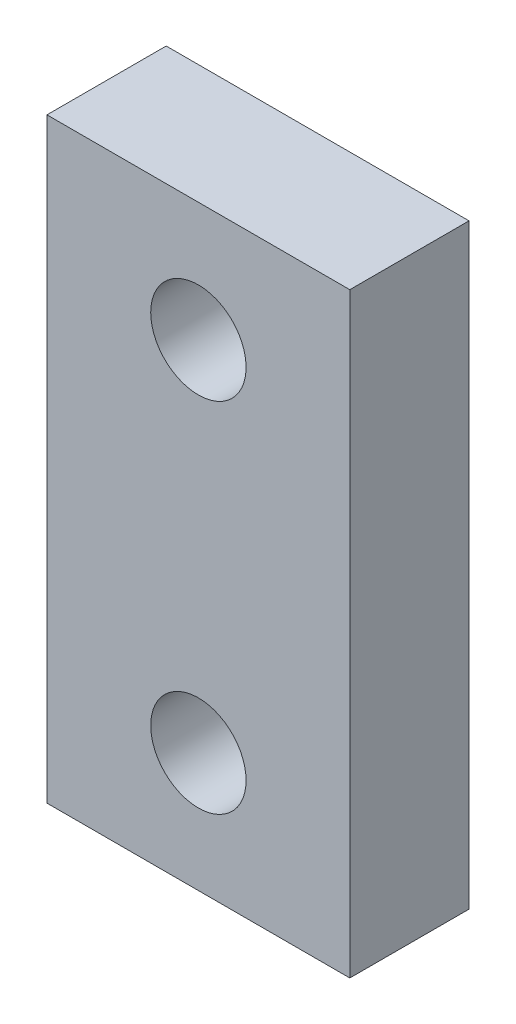
SolidWorks part; units mm, degrees
ref_plane "Front Plane" through (0, 0, 0) normal (0, 0, 1) x (1, 0, 0)
ref_plane "Top Plane" through (0, 0, 0) normal (0, 1, 0) x (1, 0, 0)
ref_plane "Right Plane" through (0, 0, 0) normal (1, 0, 0) x (0, 0, -1)
sketch "Sketch1" plane through (0, 0, 0) normal (0, 0, 1) x (1, 0, 0)
  line L0 (6.35, 0) -> (-6.35, 0) construction
  line L1 (-6.35, -12.5) -> (6.35, -12.5)
  line L2 (-6.35, -12.5) -> (-6.35, 12.5)
  line L3 (-6.35, 12.5) -> (6.35, 12.5)
  line L4 (6.35, -12.5) -> (6.35, 12.5)
  line L5 (-6.35, -12.5) -> (6.35, 12.5) construction
  line L6 (-6.35, 12.5) -> (6.35, -12.5) construction
  circle A0 centre (0, -7.5) radius 2
  circle A1 centre (0, 7.5) radius 2
  point P0 (0, 0)
  dimension "D3" = 4
  dimension "D4" = 7.5
  dimension "D1" = 12.7
  dimension "D2" = 25
extrude "Boss-Extrude1" add sketch "Sketch1" along normal blind 5
